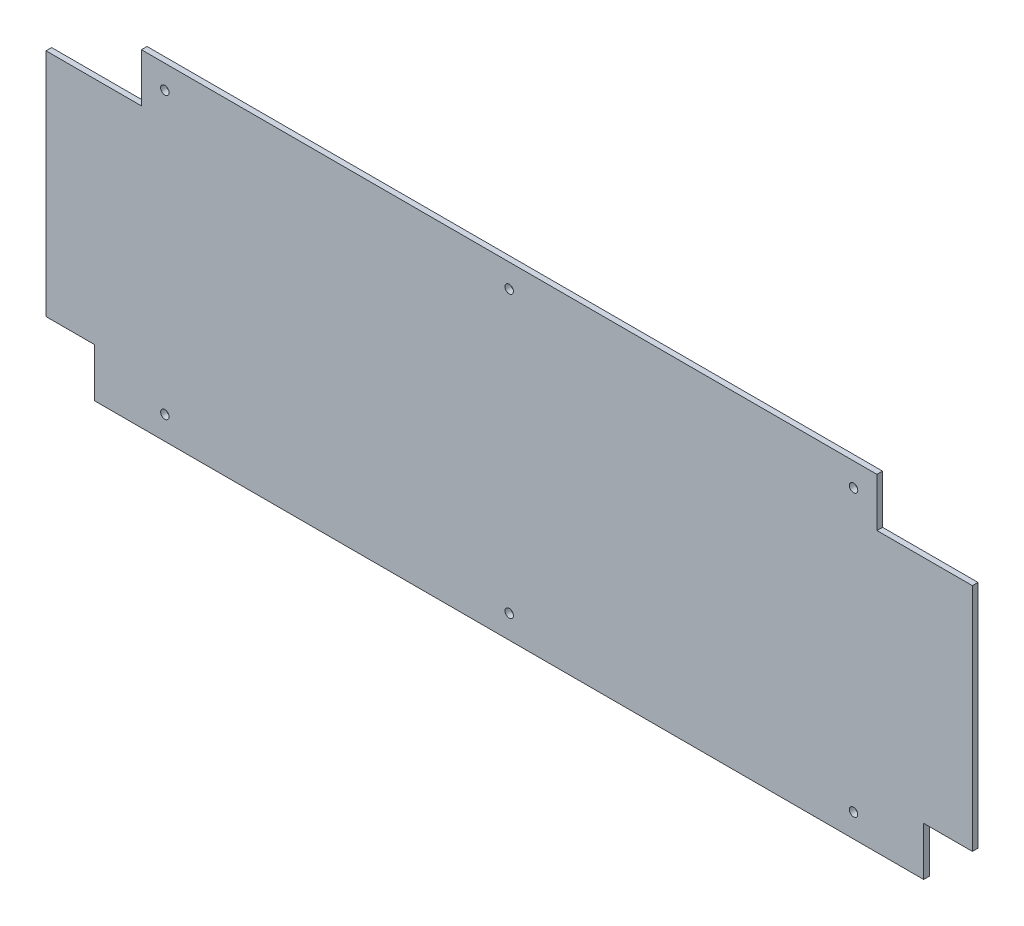
SolidWorks part; units mm, degrees
material "Acrylic (Medium-high impact)"
ref_plane "Front Plane" through (0, 0, 0) normal (0, 0, 1) x (1, 0, 0)
ref_plane "Top Plane" through (0, 0, 0) normal (0, 1, 0) x (1, 0, 0)
ref_plane "Right Plane" through (0, 0, 0) normal (1, 0, 0) x (0, 0, -1)
sketch "Sketch1" plane through (0, 0, 0) normal (0, 0, 1) x (1, 0, 0)
  line L0 (500.6453, 100) -> (500.6453, 250) construction
  line L1 (31.6453, 0) -> (474.6453, 0)
  line L2 (5.6453, 26) -> (5.6453, 149)
  line L3 (56.6453, 175) -> (449.6453, 175)
  line L4 (500.6453, 26) -> (500.6453, 149)
  line L5 (25.6453, 175) -> (475.6453, 175) construction
  line L9 (500.6453, 149) -> (449.6453, 149)
  line L10 (449.6453, 175) -> (449.6453, 149)
  line L13 (500.6453, 26) -> (474.6453, 26)
  line L14 (474.6453, 0) -> (474.6453, 26)
  line L17 (5.6453, 26) -> (31.6453, 26)
  line L18 (31.6453, 0) -> (31.6453, 26)
  line L21 (5.6453, 149) -> (56.6453, 149)
  line L22 (56.6453, 175) -> (56.6453, 149)
  dimension "D1" = 26
  dimension "D2" = 51
  dimension "D3" = 26
  dimension "D4" = 26
  dimension "D5" = 26
  dimension "D6" = 26
  dimension "D7" = 51
  dimension "D8" = 26
extrude "Boss-Extrude1" add sketch "Sketch1" along normal blind 3
hole_wizard "M4 Clearance Hole1" positions "Sketch2" profile "Sketch3" hole size "M4" standard "ANSI Metric" end condition through all
sketch "Sketch2" plane through (0, 0, 3) normal (0, 0, 1) x (1, 0, 0)
  line L3 (31.6453, 0) -> (474.6453, 0) construction
  line L4 (31.6453, 26) -> (31.6453, 0) construction
  line L5 (474.6453, 0) -> (474.6453, 26) construction
  line L6 (31.6453, 0) -> (474.6453, 0) construction
  line L7 (449.6453, 175) -> (56.6453, 175) construction
  point P6 (253.1453, 12.5)
  point P16 (253.1453, 162.5)
  point P42 (253.1453, 0)
  point P50 (437.1453, 12.5)
  point P52 (437.1453, 162.5)
  point P54 (69.1453, 162.5)
  point P56 (69.1453, 12.5)
  dimension "D1" = 37.5
  dimension "D2" = 37.5
  dimension "D3" = 12.5
  dimension "D4" = 12.5
sketch "Sketch3" plane through (253.1453, 12.5, 3) normal (1, 0, 0) x (0, -1, 0)
  line L0 (0, 0) -> (0, 3)
  line L1 (0, 3) -> (2.25, 3)
  line L2 (2.25, 3) -> (2.25, 0)
  line L5 (2.25, 0) -> (0, 0)
  line L11 (0, -6.35) -> (0, 107.95) construction
  dimension "Thru Hole Dia." = 4.5
  dimension "Thru Hole Depth" = 3
